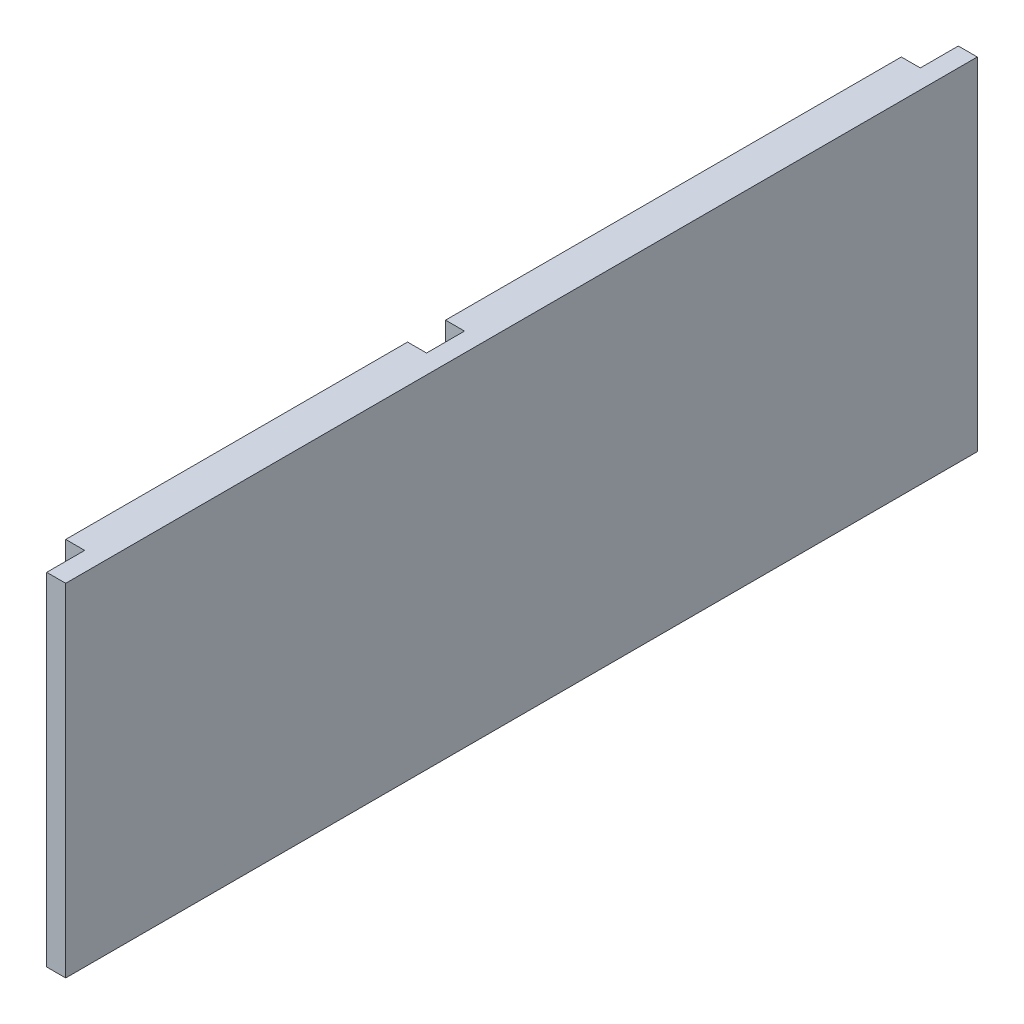
SolidWorks part; units mm, degrees
ref_plane "Front Plane" through (0, 0, 0) normal (0, 0, 1) x (1, 0, 0)
ref_plane "Top Plane" through (0, 0, 0) normal (0, 1, 0) x (1, 0, 0)
ref_plane "Right Plane" through (0, 0, 0) normal (1, 0, 0) x (0, 0, -1)
sketch "Sketch1" plane through (0, 0, 0) normal (1, 0, 0) x (0, 0, -1)
  line L1 (0, 0) -> (304.8, 0)
  line L2 (0, 0) -> (0, 114.3)
  line L3 (0, 114.3) -> (304.8, 114.3)
  line L4 (304.8, 0) -> (304.8, 114.3)
  dimension "D1" = 304.8
  dimension "D2" = 114.3
extrude "Boss-Extrude1" add sketch "Sketch1" along normal blind 12.7
sketch "Sketch2" plane through (0, 0, 0) normal (-1, 0, 0) x (0, 0, 1)
  line L0 (0, 0) -> (-304.8, 0) construction
  line L1 (0, 114.3) -> (-12.7, 114.3)
  line L2 (0, 114.3) -> (0, 0)
  line L3 (0, 0) -> (-12.7, 0)
  line L4 (-12.7, 114.3) -> (-12.7, 0)
  line L5 (-304.8, 114.3) -> (0, 114.3) construction
  line L6 (-304.8, 114.3) -> (-292.1, 114.3)
  line L7 (-304.8, 114.3) -> (-304.8, 0)
  line L8 (-304.8, 0) -> (-292.1, 0)
  line L9 (-292.1, 114.3) -> (-292.1, 0)
  line L10 (-304.8, 0) -> (-304.8, 114.3) construction
  line L11 (-139.7, 114.3) -> (-127, 114.3)
  line L12 (-139.7, 114.3) -> (-139.7, 0)
  line L13 (-139.7, 0) -> (-127, 0)
  line L14 (-127, 114.3) -> (-127, 0)
  dimension "D1" = 12.7
  dimension "D2" = 12.7
  dimension "D3" = 12.7
  dimension "D4" = 152.4
extrude "Cut-Extrude1" cut sketch "Sketch2" against normal blind 6.35
